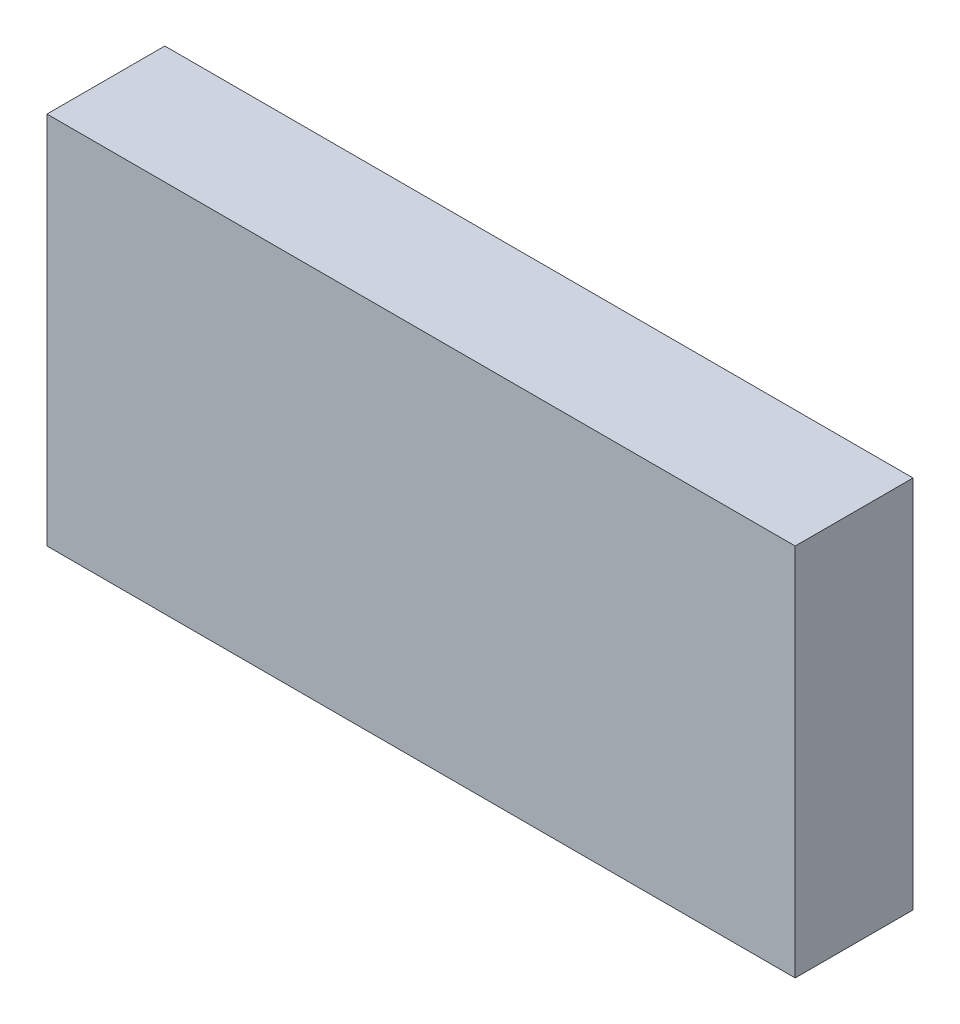
SolidWorks part; units mm, degrees
ref_plane "Front Plane" through (0, 0, 0) normal (0, 0, 1) x (1, 0, 0)
ref_plane "Top Plane" through (0, 0, 0) normal (0, 1, 0) x (1, 0, 0)
ref_plane "Right Plane" through (0, 0, 0) normal (1, 0, 0) x (0, 0, -1)
sketch "Sketch1" plane through (0, 0, 0) normal (0, 0, 1) x (1, 0, 0)
  line L1 (0, 0) -> (40, 0)
  line L2 (0, 0) -> (0, 20)
  line L3 (0, 20) -> (40, 20)
  line L4 (40, 0) -> (40, 20)
extrude "Boss-Extrude1" add sketch "Sketch1" against normal blind 6.3
